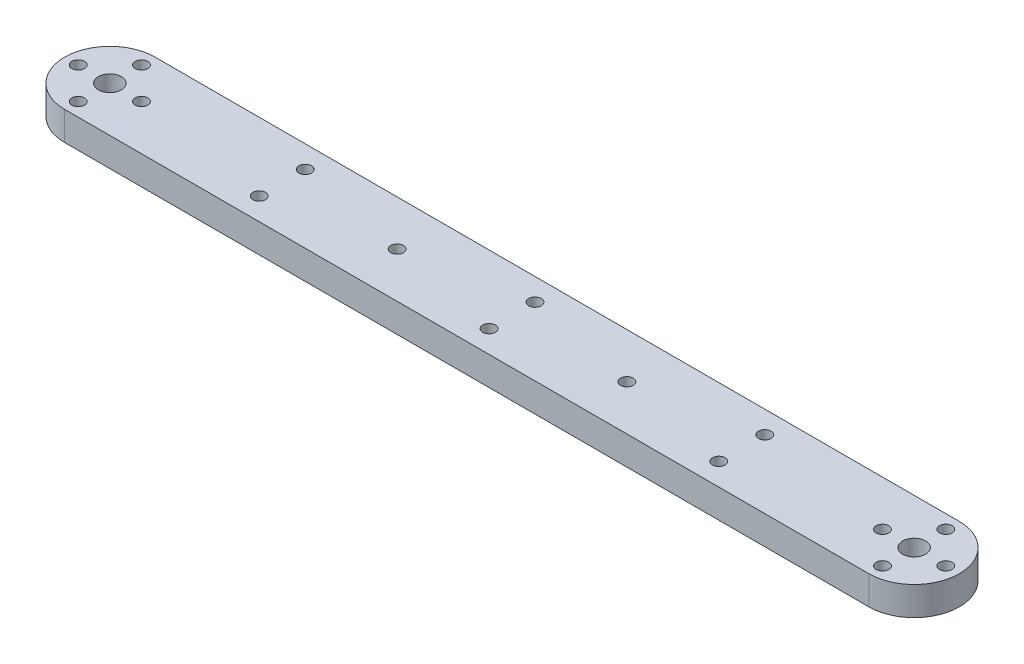
SolidWorks part; units mm, degrees
ref_plane "Front Plane" through (0, 0, 0) normal (0, 0, 1) x (1, 0, 0)
ref_plane "Top Plane" through (0, 0, 0) normal (0, 1, 0) x (1, 0, 0)
ref_plane "Right Plane" through (0, 0, 0) normal (1, 0, 0) x (0, 0, -1)
sketch "Sketch1" plane through (0, 0, 0) normal (0, 1, 0) x (1, 0, 0)
  line L0 (0, 0) -> (177.8, 0) construction
  line L1 (-3.4925, 0) -> (3.4925, 0) construction
  line L2 (0, 10) -> (177.8, 10)
  line L3 (0, -10) -> (177.8, -10)
  line L4 (88.9, 10) -> (88.9, -10) construction
  line L5 (-33.2205, 0) -> (214.1012, 0) construction
  line L6 (63.5, 10) -> (63.5, -10) construction
  arc A0 (0, 10) -> (0, -10) centre (0, 0) ccw
  arc A1 (177.8, -10) -> (177.8, 10) centre (177.8, 0) ccw
  circle A2 centre (0, 0) radius 7 construction
  circle A3 centre (-7, 0) radius 1.397
  circle A4 centre (0, 0) radius 2.54
  circle A5 centre (0, 7) radius 1.397
  circle A6 centre (7, 0) radius 1.397
  circle A7 centre (0, -7) radius 1.397
  circle A8 centre (177.8, 7) radius 1.397
  circle A9 centre (184.8, 0) radius 1.397
  circle A10 centre (177.8, -7) radius 1.397
  circle A11 centre (177.8, 0) radius 2.54
  circle A12 centre (170.8, 0) radius 1.397
  circle A13 centre (88.9, 5.08) radius 1.397
  circle A14 centre (88.9, -5.08) radius 1.397
  circle A15 centre (63.5, 0) radius 1.397
  circle A16 centre (38.1, 5.08) radius 1.397
  circle A17 centre (38.1, -5.08) radius 1.397
  circle A18 centre (114.3, 0) radius 1.397
  circle A19 centre (139.7, 5.08) radius 1.397
  circle A20 centre (139.7, -5.08) radius 1.397
  point P5 (88.9, 0)
  point P23 (0, 0)
  dimension "D3" = 14
  dimension "D4" = 2.794
  dimension "D5" = 5.08
  dimension "D7" = 2.794
  dimension "D10" = 2.794
  dimension "D1" = 177.8
  dimension "D2" = 20
  dimension "D8" = 5.08
  dimension "D9" = 25.4
  dimension "D6" = 4
extrude "Boss-Extrude1" add sketch "Sketch1" along normal blind 6.35
